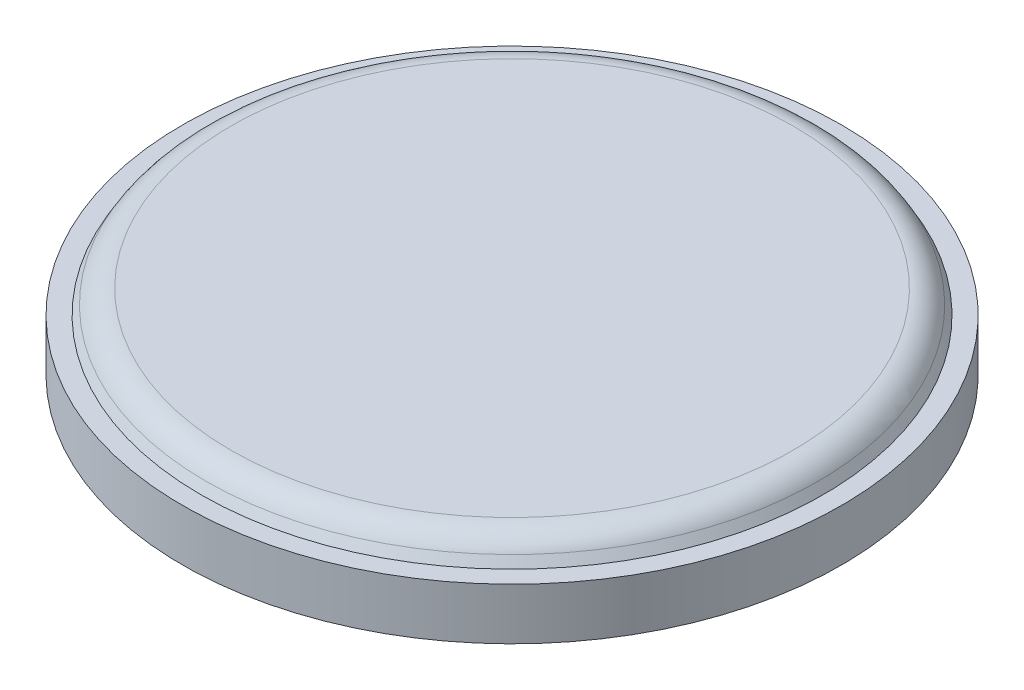
SolidWorks part; units mm, degrees
material "Glass"
ref_plane "Front Plane" through (0, 0, 0) normal (1, 0, 0) x (0, 1, 0)
ref_plane "Top Plane" through (0, 0, 0) normal (0, 0, 1) x (0, 1, 0)
ref_plane "Right Plane" through (0, 0, 0) normal (0, 1, 0) x (-1, 0, 0)
sketch "Sketch1" plane through (0, 0, 0) normal (1, 0, 0) x (0, 1, 0)
  line L0 (0, 75.1614) -> (0, -85.5025) construction
  line L1 (-88.8556, 0) -> (120.7389, 0) construction
  line L2 (15.9417, 0) -> (0, 0)
  line L3 (0, 0) -> (0, 57.1908)
  line L4 (0, 57.1908) -> (8.96, 57.1908)
  line L7 (13.02, 48.76) -> (13.02, 0)
  line L8 (13.02, 0) -> (0, 0)
  line L9 (8.96, 57.1908) -> (8.96, 53.9908)
  line L10 (8.96, 53.9908) -> (10.52, 53.0901)
  line L11 (10.52, 53.0901) -> (13.02, 51.6468) construction
  line L12 (13.02, 51.6468) -> (13.02, 48.76) construction
  arc A1 (13.02, 48.76) -> (10.52, 53.0901) centre (8.02, 48.76) ccw
  dimension "D6" = 10
  dimension "D1" = 120
  dimension "D2" = 3.2
  dimension "D3" = 8.96
  dimension "D4" = 4.06
  dimension "D5" = 48.76
revolve "Revolve1" add sketch "Sketch1" angle 360 about L1
shell "Shell1" thickness 1
sketch "Sketch2" plane through (0, 0, 0) normal (1, 0, 0) x (0, 1, 0)
  line L0 (7.96, 53.4134) -> (4.96, 53.4134)
  line L1 (7.96, -56.1908) -> (7.96, -53.4134)
  line L2 (7.96, 53.4134) -> (7.96, 56.1908)
  line L3 (4.96, 53.4134) -> (2.96, 51.4134)
  line L4 (2.96, 51.4134) -> (2.96, 31.4134)
  line L5 (2.96, 31.4134) -> (6.02, 28.3534)
  line L6 (6.02, 28.3534) -> (13.02, 28.3534)
  line L7 (13.02, -48.76) -> (13.02, 48.76) construction
  line L8 (7.96, 56.1908) -> (0, 53.304)
  line L9 (0, -56.1908) -> (7.96, -56.1908)
  line L10 (0, -56.1908) -> (7.96, -56.1908)
  line L11 (-18.8706, 0) -> (32.3738, 0) construction
  line L12 (7.96, 53.4134) -> (7.96, 56.1908)
  line L13 (7.96, -56.1908) -> (7.96, -53.4134)
  line L14 (12.02, -48.76) -> (12.02, 48.76)
  line L15 (12.02, -48.76) -> (12.02, 48.76)
  line L16 (10.02, 52.2241) -> (7.96, 53.4134)
  line L17 (7.96, -53.4134) -> (10.02, -52.2241)
  line L18 (7.96, -53.4134) -> (10.02, -52.2241)
  line L19 (10.02, 52.2241) -> (7.96, 53.4134)
  line L20 (7.96, 55.4134) -> (4.1316, 55.4134)
  line L21 (4.1316, 55.4134) -> (0.96, 52.2419)
  line L22 (0.96, 52.2419) -> (0.96, 30.585)
  line L23 (0.96, 30.585) -> (5.1916, 26.3534)
  line L24 (5.1916, 26.3534) -> (13.02, 26.3534)
  arc A0 (12.02, 48.76) -> (10.02, 52.2241) centre (8.02, 48.76) ccw
  arc A1 (10.02, -52.2241) -> (12.02, -48.76) centre (8.02, -48.76) ccw
  arc A2 (10.02, -52.2241) -> (12.02, -48.76) centre (8.02, -48.76) ccw
  arc A3 (12.02, 48.76) -> (10.02, 52.2241) centre (8.02, 48.76) ccw
  dimension "D1" = 20
  dimension "D2" = 7
  dimension "D3" = 45
  dimension "D4" = 45
  dimension "D5" = 5
  dimension "D6" = 3
  dimension "D7" = 2
revolve "Revolve2" add sketch "Sketch2" angle 360 about L11
sketch "Sketch3" plane through (0, 0.96, 0) normal (0, 1, 0) x (-1, 0, 0)
  line L1 (60.1111, 0) -> (-63.2586, 0) construction
  circle A1 centre (41.38, 0) radius 4
  dimension "D2" = 8
  dimension "D1" = 41.38
extrude "Cut-Extrude3" cut sketch "Sketch3" along normal blind 2
pattern_circular "CirPattern1" count 30 over 360 about axis through (0, 0, 0) along (0, 1, 0) of "Cut-Extrude3"
